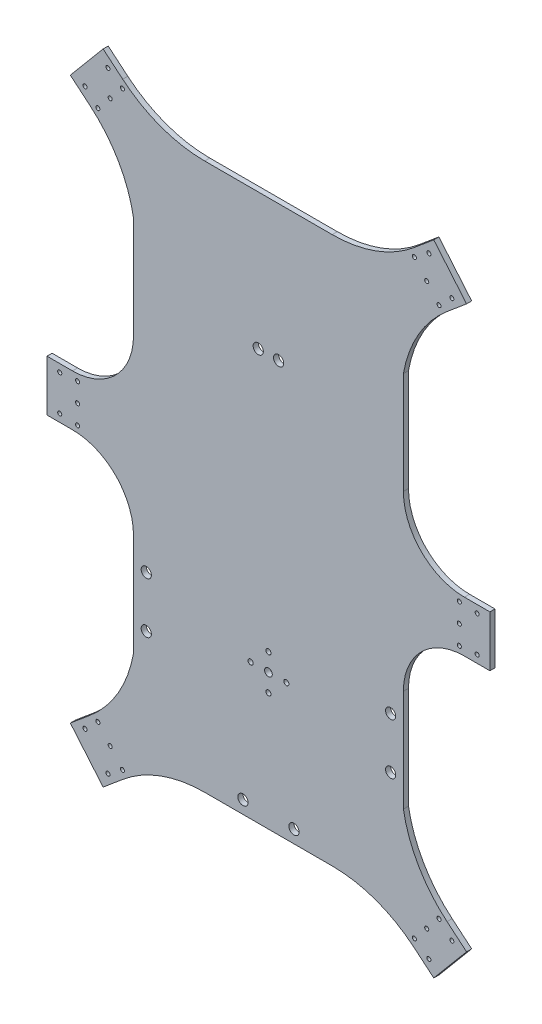
SolidWorks part; units mm, degrees
other "标注1"
sketch "草图5" plane through (86.8093, -18.1257, 0) normal (0.1619, -0.0079, -0.9868) x (-0.6314, -0.7693, -0.0975)
other "标注2"
sketch "草图6" plane through (86.8093, -18.1257, 0) normal (0.1619, -0.0079, -0.9868) x (-0.6314, -0.7693, -0.0975)
ref_plane "前视基准面" through (0, 0, 0) normal (0, 0, 1) x (1, 0, 0)
ref_plane "上视基准面" through (0, 0, 0) normal (0, 1, 0) x (1, 0, 0)
ref_plane "右视基准面" through (0, 0, 0) normal (1, 0, 0) x (0, 0, -1)
sketch "草图1" plane through (0, 0, 0) normal (0, 0, 1) x (1, 0, 0)
  line L0 (-52.8941, 33.2429) -> (-52.8941, 73.2429)
  line L1 (-25, 0) -> (25, 0)
  line L2 (-76.8093, 97.1581) -> (-86.8093, 97.1581)
  line L3 (-57.1394, -11.6978) -> (-64.7998, -18.1257)
  line L4 (-64.7998, -18.1257) -> (-77.6556, -2.8048)
  line L5 (-77.6556, -2.8048) -> (-69.9951, 3.6231)
  line L6 (-86.8093, 97.1581) -> (-86.8093, 117.1581)
  line L7 (-86.8093, 117.1581) -> (-76.8093, 117.1581)
  line L9 (-25, 214.3162) -> (25, 214.3162)
  line L10 (-57.1394, 226.0139) -> (-64.7998, 232.4418)
  line L11 (-64.7998, 232.4418) -> (-77.6556, 217.1209)
  line L12 (-77.6556, 217.1209) -> (-69.9951, 210.6931)
  line L13 (-52.8941, 181.0732) -> (-52.8941, 141.0732)
  line L14 (57.1394, -11.6978) -> (64.7998, -18.1257)
  line L15 (52.8941, 181.0732) -> (52.8941, 141.0732)
  line L16 (77.6556, 217.1209) -> (69.9951, 210.6931)
  line L17 (64.7998, 232.4418) -> (77.6556, 217.1209)
  line L18 (57.1394, 226.0139) -> (64.7998, 232.4418)
  line L19 (86.8093, 117.1581) -> (76.8093, 117.1581)
  line L20 (86.8093, 97.1581) -> (86.8093, 117.1581)
  line L21 (77.6556, -2.8048) -> (69.9951, 3.6231)
  line L22 (64.7998, -18.1257) -> (77.6556, -2.8048)
  line L23 (76.8093, 97.1581) -> (86.8093, 97.1581)
  line L24 (52.8941, 33.2429) -> (52.8941, 73.2429)
  arc A0 (-25, 0) -> (-57.1394, -11.6978) centre (-25, -50) ccw
  arc A1 (-52.8941, 33.2429) -> (-69.9951, 3.6231) centre (-102.1345, 41.9253) cw
  arc A2 (-52.8941, 73.2429) -> (-76.8093, 97.1581) centre (-76.8093, 73.2429) ccw
  arc A3 (-52.8941, 141.0732) -> (-76.8093, 117.1581) centre (-76.8093, 141.0732) cw
  arc A4 (-25, 214.3162) -> (-57.1394, 226.0139) centre (-25, 264.3162) cw
  arc A5 (-52.8941, 181.0732) -> (-69.9951, 210.6931) centre (-102.1345, 172.3908) ccw
  arc A6 (52.8941, 181.0732) -> (69.9951, 210.6931) centre (102.1345, 172.3908) cw
  arc A7 (25, 214.3162) -> (57.1394, 226.0139) centre (25, 264.3162) ccw
  arc A8 (52.8941, 141.0732) -> (76.8093, 117.1581) centre (76.8093, 141.0732) ccw
  arc A9 (52.8941, 73.2429) -> (76.8093, 97.1581) centre (76.8093, 73.2429) cw
  arc A10 (52.8941, 33.2429) -> (69.9951, 3.6231) centre (102.1345, 41.9253) ccw
  arc A11 (25, 0) -> (57.1394, -11.6978) centre (25, -50) cw
extrude "凸台-拉伸1" add sketch "草图1" along normal blind 2
sketch "草图2" plane through (0, 0, 2) normal (0, 0, 1) x (1, 0, 0)
  line L0 (77.6556, 217.1209) -> (64.7998, 232.4418) construction
  line L6 (64.7998, 232.4418) -> (57.1394, 226.0139) construction
  line L8 (69.9951, 210.6931) -> (77.6556, 217.1209) construction
  line L9 (-64.7998, 232.4418) -> (-77.6556, 217.1209) construction
  line L10 (-77.6556, 217.1209) -> (-69.9951, 210.6931) construction
  line L11 (-57.1394, 226.0139) -> (-64.7998, 232.4418) construction
  line L12 (-86.8093, 117.1581) -> (-86.8093, 97.1581) construction
  line L13 (-86.8093, 97.1581) -> (-76.8093, 97.1581) construction
  line L14 (-76.8093, 117.1581) -> (-86.8093, 117.1581) construction
  line L15 (86.8093, 97.1581) -> (86.8093, 117.1581) construction
  line L16 (76.8093, 97.1581) -> (86.8093, 97.1581) construction
  line L17 (86.8093, 117.1581) -> (76.8093, 117.1581) construction
  line L18 (64.7998, -18.1257) -> (77.6556, -2.8048) construction
  line L19 (57.1394, -11.6978) -> (64.7998, -18.1257) construction
  line L20 (77.6556, -2.8048) -> (69.9951, 3.6231) construction
  line L21 (-77.6556, -2.8048) -> (-64.7998, -18.1257) construction
  line L22 (-69.9951, 3.6231) -> (-77.6556, -2.8048) construction
  line L23 (-64.7998, -18.1257) -> (-57.1394, -11.6978) construction
  circle A0 centre (-62.0352, 217.0679) radius 0.8
  circle A1 centre (-71.897, 216.2051) radius 0.8
  circle A2 centre (-62.898, 226.9297) radius 0.8
  circle A3 centre (-81.8093, 100.1581) radius 0.8
  circle A4 centre (-74.8093, 107.1581) radius 0.8
  circle A5 centre (-81.8093, 114.1581) radius 0.8
  circle A6 centre (81.8093, 114.1581) radius 0.8
  circle A7 centre (74.8093, 107.1581) radius 0.8
  circle A8 centre (81.8093, 100.1581) radius 0.8
  circle A9 centre (71.897, 216.2051) radius 0.8
  circle A10 centre (62.0352, 217.0679) radius 0.8
  circle A11 centre (62.898, 226.9297) radius 0.8
  circle A12 centre (71.897, -1.889) radius 0.8
  circle A13 centre (62.0352, -2.7518) radius 0.8
  circle A14 centre (62.898, -12.6136) radius 0.8
  circle A15 centre (-71.897, -1.889) radius 0.8
  circle A16 centre (-62.0352, -2.7518) radius 0.8
  circle A17 centre (-62.898, -12.6136) radius 0.8
  circle A18 centre (-47.8941, 63.2429) radius 2
  circle A19 centre (-47.8941, 43.2429) radius 2
  circle A20 centre (47.8941, 43.2429) radius 2
  circle A21 centre (47.8941, 63.2429) radius 2
  circle A22 centre (-10, 5) radius 2
  circle A23 centre (10, 5) radius 2
  circle A24 centre (-74.8093, 114.6581) radius 0.8
  circle A25 centre (-74.8093, 99.6581) radius 0.8
  circle A26 centre (74.8093, 114.6581) radius 0.8
  circle A27 centre (74.8093, 99.6581) radius 0.8
  circle A28 centre (66.8561, 2.9936) radius 0.8
  circle A29 centre (57.2143, -8.4971) radius 0.8
  circle A30 centre (-57.2143, -8.4971) radius 0.8
  circle A31 centre (-66.8561, 2.9936) radius 0.8
  circle A32 centre (-57.2143, 222.8133) radius 0.8
  circle A33 centre (-66.8561, 211.3226) radius 0.8
  circle A34 centre (66.8561, 211.3226) radius 0.8
  circle A35 centre (57.2143, 222.8133) radius 0.8
  dimension "D1" = 7.5
  dimension "D2" = 7.5
  dimension "D3" = 12
  dimension "D4" = 12
  dimension "D5" = 12
  dimension "D6" = 3
  dimension "D7" = 3
  dimension "D8" = 12
  dimension "D9" = 12
  dimension "D10" = 12
  dimension "D11" = 3
  dimension "D12" = 3
  dimension "D13" = 12
  dimension "D14" = 12
  dimension "D15" = 3
  dimension "D16" = 3
  dimension "D17" = 12
  dimension "D18" = 12
  dimension "D19" = 3
  dimension "D20" = 3
  dimension "D21" = 12
  dimension "D22" = 12
  dimension "D23" = 12
  dimension "D24" = 3
  dimension "D25" = 3
  dimension "D26" = 12
  dimension "D27" = 12
  dimension "D28" = 12
  dimension "D29" = 3
  dimension "D30" = 3
extrude "切除-拉伸1" cut sketch "草图2" against normal blind 10
sketch "草图3" plane through (0, 0, 2) normal (0, 0, 1) x (1, 0, 0)
  circle A0 centre (0, 53.2429) radius 1.5
  circle A2 centre (0, 60.2429) radius 1
  circle A3 centre (7, 53.2429) radius 1
  circle A4 centre (0, 46.2429) radius 1
  circle A5 centre (-7, 53.2429) radius 1
  point P14 (0, 53.2429)
  dimension "D1" = 4
extrude "切除-拉伸2" cut sketch "草图3" against normal through all
sketch "草图4" plane through (0, 0, 2) normal (0, 0, 1) x (1, 0, 0)
  circle A2 centre (4, 161.0732) radius 2
  circle A4 centre (-4, 161.0732) radius 2
extrude "切除-拉伸3" cut sketch "草图4" against normal blind 10
